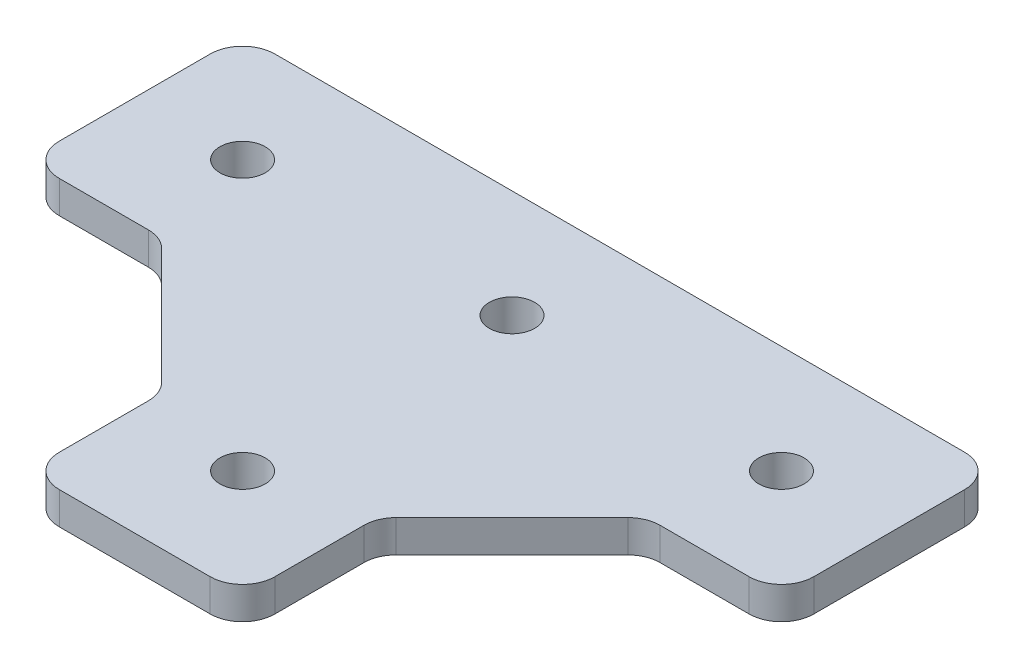
SolidWorks part; units mm, degrees
material "A-玻璃纤维"
ref_plane "前视基准面" through (0, 0, 0) normal (0, 0, 1) x (1, 0, 0)
ref_plane "上视基准面" through (0, 0, 0) normal (0, 1, 0) x (1, 0, 0)
ref_plane "右视基准面" through (0, 0, 0) normal (1, 0, 0) x (0, 0, -1)
sketch "草图1" plane through (0, 0, 0) normal (0, 1, 0) x (1, 0, 0)
  line L0 (-43.2884, 0) -> (46.6978, 0) construction
  line L1 (0, 0) -> (0, -25) construction
  line L2 (35, 10) -> (-35, 10)
  line L3 (-35, 10) -> (-35, -10)
  line L4 (-35, -10) -> (-10, -10)
  line L5 (-10, -10) -> (-10, -35)
  line L6 (-10, -35) -> (10, -35)
  line L7 (10, -35) -> (10, -10)
  line L8 (10, -10) -> (35, -10)
  line L9 (35, -10) -> (35, 10)
  line L10 (-22.5, -10) -> (-10, -22.5)
  line L11 (22.5, -10) -> (10, -22.5)
  circle A0 centre (0, 0) radius 2.1
  circle A1 centre (25, 0) radius 2.1
  circle A2 centre (-25, 0) radius 2.1
  circle A3 centre (0, -25) radius 2.1
  dimension "D1" = 4.2
  dimension "D2" = 25
  dimension "D3" = 25
  dimension "D4" = 25
  dimension "D5" = 10
  dimension "D7" = 10
  dimension "D6" = 20
  dimension "D8" = 10
  dimension "D9" = 20
extrude "凸台-拉伸1" add sketch "草图1" along normal blind 3
fillet "圆角1" radius 3 10 edges at (10, 1.5, 22.5) (10, 1.5, 35) (-10, 1.5, 35) (-10, 1.5, 22.5) (-22.5, 1.5, 10) (-35, 1.5, 10) (35, 1.5, -10) (35, 1.5, 10) (22.5, 1.5, 10) (-35, 1.5, -10)
